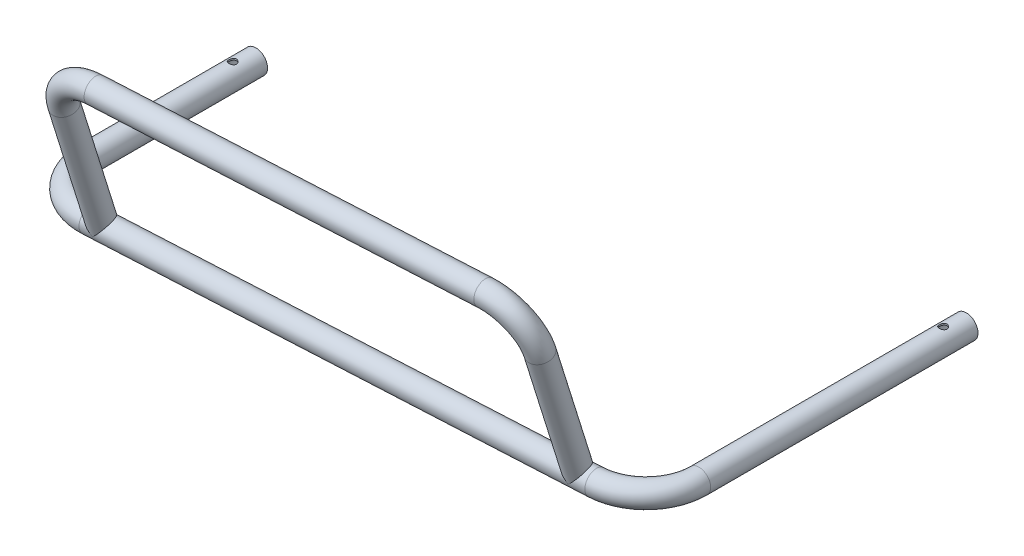
SolidWorks part; units mm, degrees
ref_plane "Front Plane" through (0, 0, 0) normal (0, 0, 1) x (1, 0, 0)
ref_plane "Top Plane" through (0, 0, 0) normal (0, 1, 0) x (1, 0, 0)
ref_plane "Right Plane" through (0, 0, 0) normal (1, 0, 0) x (0, 0, -1)
sketch3d "3DSketch1"
  line L0 (0, 0, 0) -> (0, 0, 230)
  line L1 (-43.201, 0, 275.5244) -> (-456.6337, 0, 297.1915)
  line L2 (-503, 0, 253.1915) -> (-503, 0, 108.1915)
  line L3 (-55.1448, 108.9315, 311.6467) -> (-444.1448, 108.9315, 332.0333) construction
  line L4 (-57, 0, 276.2476) -> (-55.1448, 108.9315, 311.6467)
  line L5 (-89.7805, 142.4561, 324.3862) -> (-408.3673, 142.4561, 341.0826)
  line L6 (-444.1448, 108.9315, 332.0333) -> (-446, 0, 296.6342)
  line L7 (-503, 0, 108.1915) -> (0, 0, 108.1915) construction
  line L8 (-446, 0, 296.6342) -> (-446, 0, 420.9268) construction
  line L9 (-57, 0, 276.2476) -> (-57, 0, 439.042) construction
  line L10 (0, 0, 0) -> (-389.2604, 0, 0) construction
  line L11 (-446, 0, 296.6342) -> (-443.5739, 142.4561, 342.9277) construction
  arc A0 (0, 0, 230) -> (-43.201, 0, 275.5244) centre (-45.5869, 0, 230) ccw
  arc A1 (-456.6337, 0, 297.1915) -> (-503, 0, 253.1915) centre (-458.9396, 0, 253.1915) ccw
  arc A3 (-55.1448, 108.9315, 311.6467) -> (-89.7805, 142.4561, 324.3862) centre (-90.3514, 108.9315, 313.4918) ccw
  arc A4 (-444.1448, 108.9315, 332.0333) -> (-408.3673, 142.4561, 341.0826) centre (-408.9382, 108.9315, 330.1882) cw
  point P4 (-45.5869, -45.5869, 230)
  point P8 (-458.9396, -44.0604, 253.1915)
  point P15 (-88.5969, 98.0222, 346.9704)
  point P27 (-410.6927, 119.8409, 296.7096)
  dimension "D3" = 414
  dimension "D6" = 93
  dimension "D7" = 114.554
  dimension "D8" = 108.1915
  dimension "D5" = 189
  dimension "D10" = 72
  dimension "D12" = 57
  dimension "D11" = 57
  dimension "D1" = 503
  dimension "D2" = 230
  dimension "D4" = 145
  dimension "D9" = 319.024
other "Chassis BUMPERFRAMEPROFILE(1)"
ref_plane "Plane1" through (0, 0, 0) normal (0, 0, 1) x (1, 0, 0)
sketch "Sketch21" plane through (0, 0, 0) normal (0, 0, 1) x (1, 0, 0)
  circle A0 centre (0, 0) radius 10.033
  circle A1 centre (0, 0) radius 8.763
  point P4 (0, 0)
  dimension "D1" = 20.066
  dimension "D2" = 17.526
other "Chassis BUMPERFRAMEPROFILE(3)"
ref_plane "Plane3" through (-57, 0, 276.2476) normal (0.0162, 0.9509, 0.309) x (0.9998, -0.0118, -0.0162)
sketch "Sketch2" plane through (-57, 0, 276.2476) normal (0.0162, 0.9509, 0.309) x (0.9998, -0.0118, -0.0162)
  circle A0 centre (0, 0) radius 10.033
  circle A1 centre (0, 0) radius 8.763
  point P4 (0, 0)
  dimension "D1" = 20.066
  dimension "D2" = 17.526
sketch "Sketch22" plane through (0, 0, 0) normal (0, 1, 0) x (1, 0, 0)
  line L0 (-503, -253.1915) -> (-503, -108.1915) construction
  line L1 (0, 0) -> (0, -230) construction
  circle A0 centre (-503, -128.1915) radius 3.3
  circle A1 centre (0, -20) radius 3.3
  dimension "D3" = 6.6
  dimension "D1" = 20
  dimension "D2" = 20
ref_plane "Plane4" through (0, 0, 0) normal (-1, 0, 0) x (0, 0, 1)
extrude "Cut-Extrude1" cut sketch "Sketch22" against normal through all both and the other way through all
sketch3d "3DSketch3"
  line L0 (-408.3673, 142.4561, 341.0826) -> (-404.401, 145.1062, 416.7638) construction
  line L1 (-407.8425, 142.8067, 351.0957) -> (-373.6519, 142.8067, 349.3039) construction
  line L2 (-161.6818, 142.4561, 328.1544) -> (-161.6818, 137.4231, 328.1544) construction
  line L3 (-408.3673, 132.4231, 341.0826) -> (-408.3673, 152.4891, 341.0826) construction
  line L4 (-408.3673, 137.4231, 341.0826) -> (-161.6818, 137.4231, 328.1544) construction
  line L5 (-161.6818, 137.4231, 338.3835) -> (-161.6818, 137.4231, 348.5835)
  line L6 (-161.6818, 134.5799, 351.4267) -> (-161.6818, 79.5799, 351.4267)
  line L7 (-161.6818, 79.3321, 351.4159) -> (-161.6818, 28.5262, 346.9709)
  line L8 (-161.6818, 26.5034, 345.8496) -> (-161.6818, 9.0507, 322.6892)
  line L9 (-161.6818, 6.7801, 321.5571) -> (-161.6818, -3.2199, 321.5571)
  line L11 (-161.6818, -6.0592, 318.8627) -> (-161.6818, -7.5769, 289.9025)
  line L13 (-89.7805, 142.4561, 324.3862) -> (-408.3673, 142.4561, 341.0826) construction
  line L15 (-43.201, 0, 275.5244) -> (-456.6337, 0, 297.1915) construction
  line L16 (-161.6916, 142.8067, 338.1955) -> (-161.6818, 137.4231, 338.3835) construction
  line L17 (-161.6818, 137.4231, 328.1544) -> (-161.6818, 137.4231, 338.3835)
  line L18 (-394.416, 137.4231, 340.3514) -> (-394.416, 94.2649, 340.3514) construction
  line L20 (-446, 0, 296.6342) -> (-443.5739, 142.4561, 342.9277) construction
  circle A0 centre (-408.3673, 142.4561, 341.0826) radius 10.033 construction
  arc A1 (-161.6818, 137.4231, 348.5835) -> (-161.6818, 134.5799, 351.4267) centre (-161.6818, 134.5799, 348.5835) ccw
  arc A2 (-161.6818, 79.5799, 351.4267) -> (-161.6818, 79.3321, 351.4159) centre (-161.6818, 79.5799, 348.5835) ccw
  arc A3 (-161.6818, 28.5262, 346.9709) -> (-161.6818, 26.5034, 345.8496) centre (-161.6818, 28.774, 344.1386) ccw
  arc A4 (-161.6818, 9.0507, 322.6892) -> (-161.6818, 6.7801, 321.5571) centre (-161.6818, 6.7801, 324.4002) ccw
  arc A5 (-161.6818, -3.2199, 321.5571) -> (-161.6818, -6.0592, 318.8627) centre (-161.6818, -3.2199, 318.7139) ccw
  point P2 (-407.8425, 142.8067, 351.0957)
  point P10 (-418.3865, 142.4561, 341.6077)
  point P19 (-158.8386, 134.5799, 348.5835)
  point P21 (-158.8386, 79.5799, 348.5835)
  point P27 (-164.5249, 6.7801, 324.4002)
  point P30 (-158.8386, 28.774, 344.1386)
  point P34 (-158.8386, -3.2199, 318.7139)
  dimension "D2" = 5
  dimension "D3" = 72
  dimension "D16" = 10.2
  dimension "D5" = 55
  dimension "D6" = 175
  dimension "D7" = 51
  dimension "D8" = 92
  dimension "128" = 127
  dimension "D9" = 29
  dimension "D10" = 10
  dimension "D11" = 93
  dimension "D12" = 29
  dimension "D14" = 5.033
  dimension "D15" = 145
  dimension "D4" = 49.25
